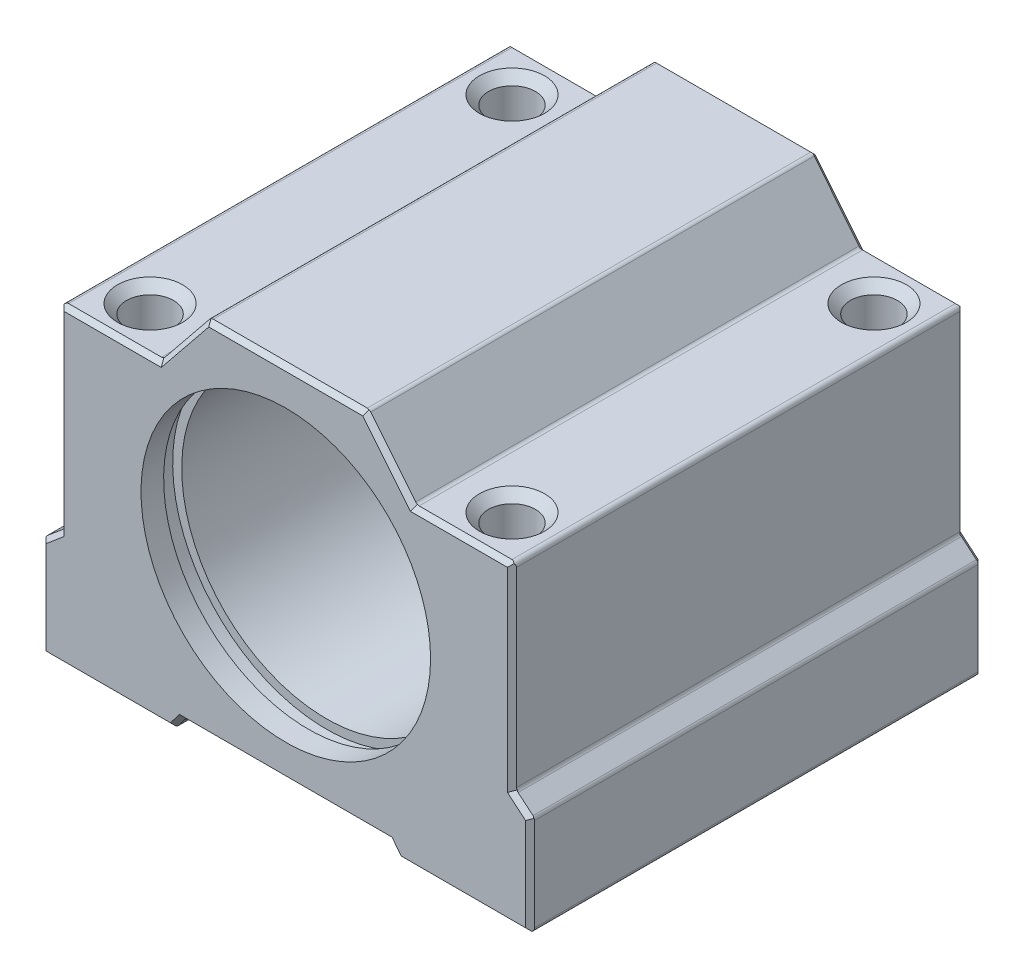
SolidWorks part; units mm, degrees
material "1060 Alloy"
ref_plane "Front Plane" through (0, 0, 0) normal (0, 0, 1) x (1, 0, 0)
ref_plane "Top Plane" through (0, 0, 0) normal (0, 1, 0) x (1, 0, 0)
ref_plane "Right Plane" through (0, 0, 0) normal (1, 0, 0) x (0, 0, -1)
sketch "Sketch1" plane through (0, 0, 0) normal (0, 0, 1) x (1, 0, 0)
  line L0 (0, -39.7) -> (-27, -39.7) construction
  line L1 (0, 0) -> (-27, 0) construction
  line L2 (0, 0) -> (0, -41) construction
  line L3 (0, -41) -> (-27, -41) construction
  line L4 (-27, 0) -> (-27, -41) construction
  line L5 (-25, 0) -> (-25, -41) construction
  line L6 (-27, -6.5) -> (0, -6.5) construction
  line L7 (-8.75, 0) -> (-8.75, -41) construction
  line L8 (-14, 0) -> (-14, -41) construction
  line L9 (8.75, 0) -> (-8.75, 0)
  line L10 (-8.75, 0) -> (-14, -6.5)
  line L11 (-14, -6.5) -> (-25, -6.5)
  line L12 (-27, -30) -> (0, -30) construction
  line L13 (-27, -41) -> (-27, -30)
  line L14 (-27, -30) -> (-25, -28.3137)
  line L15 (-25, -28.3137) -> (-25, -6.5)
  line L16 (-12.5, 0) -> (-12.5, -41) construction
  line L17 (-12.5, -41) -> (-27, -41)
  line L18 (11.5, -39.7) -> (-11.5, -39.7)
  line L19 (-12.5, -41) -> (-11.5, -39.7)
  line L20 (12.5, -41) -> (11.5, -39.7)
  line L21 (12.5, -41) -> (27, -41)
  line L22 (27, -41) -> (27, -30)
  line L23 (27, -30) -> (25, -28.3137)
  line L24 (25, -28.3137) -> (25, -6.5)
  line L25 (14, -6.5) -> (25, -6.5)
  line L26 (8.75, 0) -> (14, -6.5)
  circle A0 centre (0, -20) radius 16
  dimension "D13" = 32
  dimension "D1" = 27
  dimension "D2" = 41
  dimension "D3" = 25
  dimension "D4" = 34.5
  dimension "D5" = 8.75
  dimension "D6" = 14
  dimension "D7" = 11
  dimension "D8" = 1.3
  dimension "D9" = 135
  dimension "D10" = 12.5
  dimension "D11" = 11.5
  dimension "D12" = 21
extrude "Boss-Extrude1" add sketch "Sketch1" along normal blind 50
sketch "Sketch2" plane through (0, 0, 0) normal (0, 1, 0) x (1, 0, 0)
  line L0 (0, 0) -> (0, -50) construction
  line L1 (-11.5, -50) -> (11.5, -50) construction
  line L2 (-27, -25) -> (27, -25) construction
  line L3 (-20, -45) -> (20, -45) construction
  line L4 (-20, -45) -> (-20, -5) construction
  line L5 (-20, -5) -> (20, -5) construction
  line L6 (20, -45) -> (20, -5) construction
  line L7 (-20, -45) -> (20, -5) construction
  line L8 (-20, -5) -> (20, -45) construction
  line L9 (-27, -50) -> (-27, 0) construction
  line L10 (27, -50) -> (27, 0) construction
  circle A0 centre (-20, -45) radius 2.6
  circle A1 centre (20, -45) radius 2.6
  circle A2 centre (20, -5) radius 2.6
  circle A3 centre (-20, -5) radius 2.6
  point P5 (0, -25)
  dimension "D2" = 5.2
  dimension "D1" = 40
extrude "Cut-Extrude1" cut sketch "Sketch2" against normal up to next
ref_plane "Bottom Plane" through (0, -41, 0) normal (0, -1, 0) x (1, 0, 0)
sketch "Sketch3" plane through (0, -41, 0) normal (0, -1, 0) x (1, 0, 0)
  line L0 (0, 0) -> (0, 50) construction
  line L1 (-11.5, 50) -> (11.5, 50) construction
  line L2 (-27, 25) -> (27, 25) construction
  line L3 (-20, 45) -> (20, 45) construction
  line L4 (-20, 45) -> (-20, 5) construction
  line L5 (-20, 5) -> (20, 5) construction
  line L6 (20, 45) -> (20, 5) construction
  line L7 (-20, 45) -> (20, 5) construction
  line L8 (-20, 5) -> (20, 45) construction
  line L9 (-27, 50) -> (-27, 0) construction
  line L10 (27, 50) -> (27, 0) construction
  circle A0 centre (-20, 45) radius 3
  circle A1 centre (20, 45) radius 3
  circle A2 centre (20, 5) radius 3
  circle A3 centre (-20, 5) radius 3
  point P5 (0, 25)
  dimension "D2" = 6
  dimension "D1" = 40
extrude "Cut-Extrude2" cut sketch "Sketch3" against normal blind 12
sketch "Sketch4" plane through (0, 0, 0) normal (1, 0, 0) x (0, 0, -1)
  line L0 (-25, 0) -> (-25, -41) construction
  line L1 (-50, 0) -> (0, 0) construction
  line L2 (-27.5, -41) -> (27.5, -41) construction
  line L3 (-25, 0) -> (-50, 0) construction
  line L4 (-50, 0) -> (-50, -4) construction
  line L5 (-50, -4) -> (0, -4) construction
  line L6 (0, -6.5) -> (0, 0) construction
  line L7 (0, -20) -> (-50, -20) construction
  line L8 (-47.5, -4) -> (-45.5, -4)
  line L9 (-47.5, -4) -> (-47.5, -3)
  line L10 (-47.5, -3) -> (-45.5, -3)
  line L11 (-45.5, -4) -> (-45.5, -3)
  line L13 (0, -28.3137) -> (0, -6.5) construction
  line L15 (-50, -28.3137) -> (-50, -6.5) construction
  line L16 (-2.5, -4) -> (-2.5, -3)
  line L17 (-2.5, -4) -> (-4.5, -4)
  line L18 (-4.5, -4) -> (-4.5, -3)
  line L19 (-2.5, -3) -> (-4.5, -3)
  dimension "D1" = 4
  dimension "D2" = 2.5
  dimension "D3" = 2
  dimension "D4" = 16
  dimension "D5" = 17
revolve "Cut-Revolve1" cut sketch "Sketch4" angle 360 about L7
chamfer "Chamfer1" distance 1 angle 45 8 edges at (-20, -41, 8) (-20, -41, 42) (20, -41, 2) (20, -41, 48) (22.6, -6.5, 45) (22.6, -6.5, 5) (-20, -6.5, 2.4) (-20, -6.5, 42.4)
chamfer "Chamfer2" distance 0.5 angle 45 33 edges at (19.5, -6.5, 50) (11.375, -3.25, 50) (0, 0, 50) (-11.375, -3.25, 50) (-19.5, -6.5, 50) (-25, -17.4069, 50) (-26, -29.1569, 50) (-27, -35.5, 50) (-19.75, -41, 50) (-12, -40.35, 50) (0, -39.7, 50) (12, -40.35, 50) (19.75, -41, 50) (27, -35.5, 50) (26, -29.1569, 50) (25, -17.4069, 50) (16, -20, 0) (19.5, -6.5, 0) (25, -17.4069, 0) (26, -29.1569, 0) (27, -35.5, 0) (19.75, -41, 0) (12, -40.35, 0) (0, -39.7, 0) (-12, -40.35, 0) (-19.75, -41, 0) (-27, -35.5, 0) (-26, -29.1569, 0) (-25, -17.4069, 0) (-19.5, -6.5, 0) (-11.375, -3.25, 0) (0, 0, 0) (11.375, -3.25, 0)
fillet "Fillet2" radius 0.5 16 edges at (-8.75, 0, 25) (-14, -6.5, 25) (-25, -6.5, 25) (-25, -28.3137, 25) (-27, -30, 25) (-27, -41, 25) (-12.5, -41, 25) (-11.5, -39.7, 25) (11.5, -39.7, 25) (12.5, -41, 25) (27, -41, 25) (27, -30, 25) (25, -28.3137, 25) (25, -6.5, 25) (14, -6.5, 25) (8.75, 0, 25)
